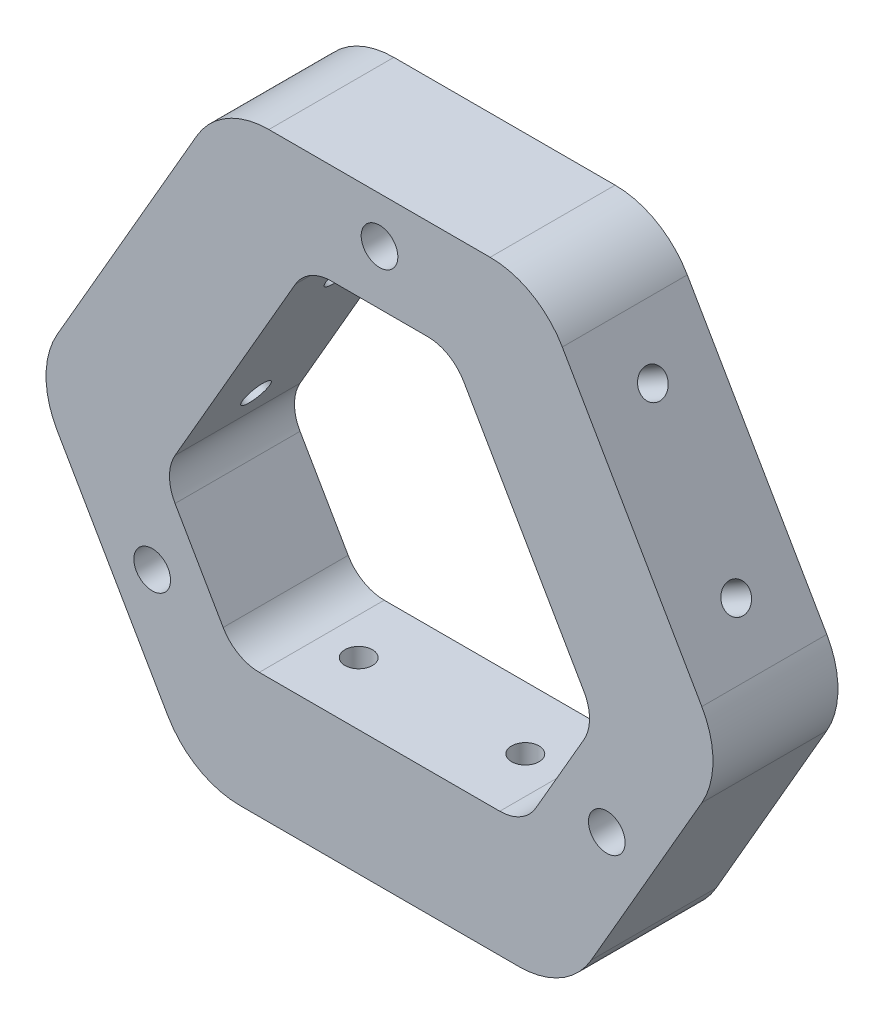
SolidWorks part; units mm, degrees
material "PLA"
ref_plane "前视基准面" through (0, 0, 0) normal (0, 0, 1) x (1, 0, 0)
ref_plane "上视基准面" through (0, 0, 0) normal (0, 1, 0) x (1, 0, 0)
ref_plane "右视基准面" through (0, 0, 0) normal (1, 0, 0) x (0, 0, -1)
other "Configuration Table"
sketch "草图1" plane through (0, 0, 0) normal (0, 0, 1) x (1, 0, 0)
  line L0 (0, 70) -> (-60.6218, -35)
  line L5 (-60.6218, -35) -> (60.6218, -35)
  line L6 (60.6218, -35) -> (0, 70)
  line L11 (0, 70) -> (0, 0) construction
  line L12 (0, 0) -> (30.3109, 17.5) construction
  line L13 (0, 0) -> (0, -35) construction
  line L14 (0, 40) -> (-34.641, -20)
  line L15 (-34.641, -20) -> (34.641, -20)
  line L16 (34.641, -20) -> (0, 40)
  line L17 (34.641, -20) -> (47.6314, -12.5) construction
  line L18 (34.641, -20) -> (34.641, -35) construction
  dimension "D1" = 15
  dimension "D2" = 35
extrude "凸台-拉伸1" add sketch "草图1" along normal blind 15
fillet "圆角1" radius 10 3 edges at (-60.6218, -35, 7.5) (60.6218, -35, 7.5) (0, 70, 7.5)
fillet "圆角2" radius 5 3 edges at (34.641, -20, 7.5) (-34.641, -20, 7.5) (0, 40, 7.5)
sketch "草图2" plane through (0, -35, 0) normal (0, -1, 0) x (1, 0, 0)
  line L0 (0, 0) -> (0, 36.777) construction
  line L1 (-43.3013, 0) -> (43.3013, 0) construction
  line L2 (-43.3013, 7.5) -> (66.3455, 7.5) construction
  line L3 (-43.3013, 15) -> (-43.3013, 0) construction
  circle A0 centre (-10, 7.5) radius 1.65
  circle A1 centre (10, 7.5) radius 1.65
  dimension "D1" = 20
  dimension "D2" = 3.3
extrude "切除-拉伸1" cut sketch "草图2" against normal blind 20
sketch "草图4" plane through (30.3109, 17.5, 0) normal (0.866, 0.5, 0) x (0, 0, -1)
  line L0 (0, 0) -> (-57.8219, 0) construction
  line L1 (0, 43.3013) -> (-15, 43.3013) construction
  circle A0 centre (-7.5, 10) radius 1.65
  circle A1 centre (-7.5, -10) radius 1.65
  point P9 (-7.5, 43.3013)
  dimension "D1" = 20
  dimension "D2" = 3.3
extrude "切除-拉伸2" cut sketch "草图4" against normal blind 20
sketch "草图5" plane through (-30.3109, 17.5, 0) normal (-0.866, 0.5, 0) x (0, 0, 1)
  line L0 (0, 0) -> (38.3926, 0) construction
  line L1 (15, 43.3013) -> (0, 43.3013) construction
  circle A0 centre (7.5, 10) radius 1.65
  circle A1 centre (7.5, -10) radius 1.65
  point P9 (7.5, 43.3013)
  dimension "D1" = 20
  dimension "D2" = 3.3
extrude "切除-拉伸3" cut sketch "草图5" against normal blind 20
sketch "草图6" plane through (0, 0, 15) normal (0, 0, 1) x (1, 0, 0)
  line L0 (-17.3205, 40) -> (17.3205, 40)
  line L1 (-8.6603, 55) -> (-51.9615, -20) construction
  line L2 (51.9615, -20) -> (8.6603, 55) construction
  line L3 (43.3013, -5) -> (25.9808, -35)
  line L4 (-25.9808, -35) -> (-43.3013, -5)
  point P13 (0, 0)
  line M3 (-8.6603, 55) -> (-51.9615, -20)
  arc M4 (-51.9615, -20) -> (-43.3013, -35) centre (-43.3013, -25) ccw
  line M5 (-43.3013, -35) -> (43.3013, -35)
  arc M6 (43.3013, -35) -> (51.9615, -20) centre (43.3013, -25) ccw
  line M7 (51.9615, -20) -> (8.6603, 55)
  arc M8 (8.6603, 55) -> (-8.6603, 55) centre (0, 50) ccw
  dimension "D1" = 40
  dimension "D2" = 3
extrude "切除-拉伸4" cut sketch "草图6" against normal blind 15 contours L0 M3 M7 M8 | L4 M5 M3 M4 | L3 M7 M5 M6
sketch "草图7" plane through (0, 0, 15) normal (0, 0, 1) x (1, 0, 0)
  line L0 (-8.6603, 25) -> (8.6603, 25)
  line L1 (-4.3301, 32.5) -> (-30.3109, -12.5) construction
  line L2 (30.3109, -12.5) -> (4.3301, 32.5) construction
  line L3 (25.9808, -5) -> (17.3205, -20)
  line L4 (-17.3205, -20) -> (-25.9808, -5)
  point P13 (0, 0)
  line M9 (-30.3109, -12.5) -> (-4.3301, 32.5)
  arc M10 (-4.3301, 32.5) -> (4.3301, 32.5) centre (0, 30) cw
  line M11 (4.3301, 32.5) -> (30.3109, -12.5)
  arc M12 (30.3109, -12.5) -> (25.9808, -20) centre (25.9808, -15) cw
  line M13 (25.9808, -20) -> (-25.9808, -20)
  arc M14 (-25.9808, -20) -> (-30.3109, -12.5) centre (-25.9808, -15) cw
  dimension "D1" = 25
  dimension "D2" = 3
extrude "凸台-拉伸2" add sketch "草图7" against normal up to surface (15 mm away) contours L0 M9 M11 M10 | L4 M13 M9 M14 | L3 M11 M13 M12 up to face at (0, 0, 0)
sketch "草图8" plane through (0, 0, 15) normal (0, 0, 1) x (1, 0, 0)
  line L0 (-19.0526, 37) -> (19.0526, 37)
  line L1 (-17.3205, 40) -> (-43.3013, -5) construction
  line L2 (43.3013, -5) -> (17.3205, 40) construction
  line L3 (-17.3205, 40) -> (17.3205, 40) construction
  line L4 (41.5692, -2) -> (22.5167, -35)
  line L5 (-22.5167, -35) -> (-41.5692, -2)
  point P14 (0, 0)
  line M9 (17.3205, 40) -> (-17.3205, 40)
  line M10 (-17.3205, 40) -> (-43.3013, -5)
  line M11 (-43.3013, -5) -> (-25.9808, -35)
  line M12 (-25.9808, -35) -> (25.9808, -35)
  line M13 (25.9808, -35) -> (43.3013, -5)
  line M14 (43.3013, -5) -> (17.3205, 40)
  dimension "D1" = 3
  dimension "D2" = 3
extrude "切除-拉伸5" cut sketch "草图8" against normal through all contours L0 M10 M14 M9 | L5 M12 M10 M11 | L4 M14 M12 M13
fillet "圆角3" radius 10 6 edges at (19.0526, 37, 7.5) (41.5692, -2, 7.5) (22.5167, -35, 7.5) (-22.5167, -35, 7.5) (-41.5692, -2, 7.5) (-19.0526, 37, 7.5)
fillet "圆角4" radius 5 6 edges at (-25.9808, -5, 7.5) (-17.3205, -20, 7.5) (17.3205, -20, 7.5) (25.9808, -5, 7.5) (8.6603, 25, 7.5) (-8.6603, 25, 7.5)
sketch "草图9" plane through (0, 0, 15) normal (0, 0, 1) x (1, 0, 0)
  line L0 (0, 0) -> (0, 37) construction
  line L1 (-13.2791, 37) -> (13.2791, 37) construction
  circle A0 centre (0, 0) radius 31.5 construction
  circle A1 centre (0, 31.5) radius 2.2
  circle A2 centre (27.2798, -15.75) radius 2.2
  circle A3 centre (-27.2798, -15.75) radius 2.2
  point P14 (0, 0)
  dimension "D1" = 63
  dimension "D2" = 4.4
  dimension "D3" = 3
extrude "切除-拉伸6" cut sketch "草图9" against normal through all
